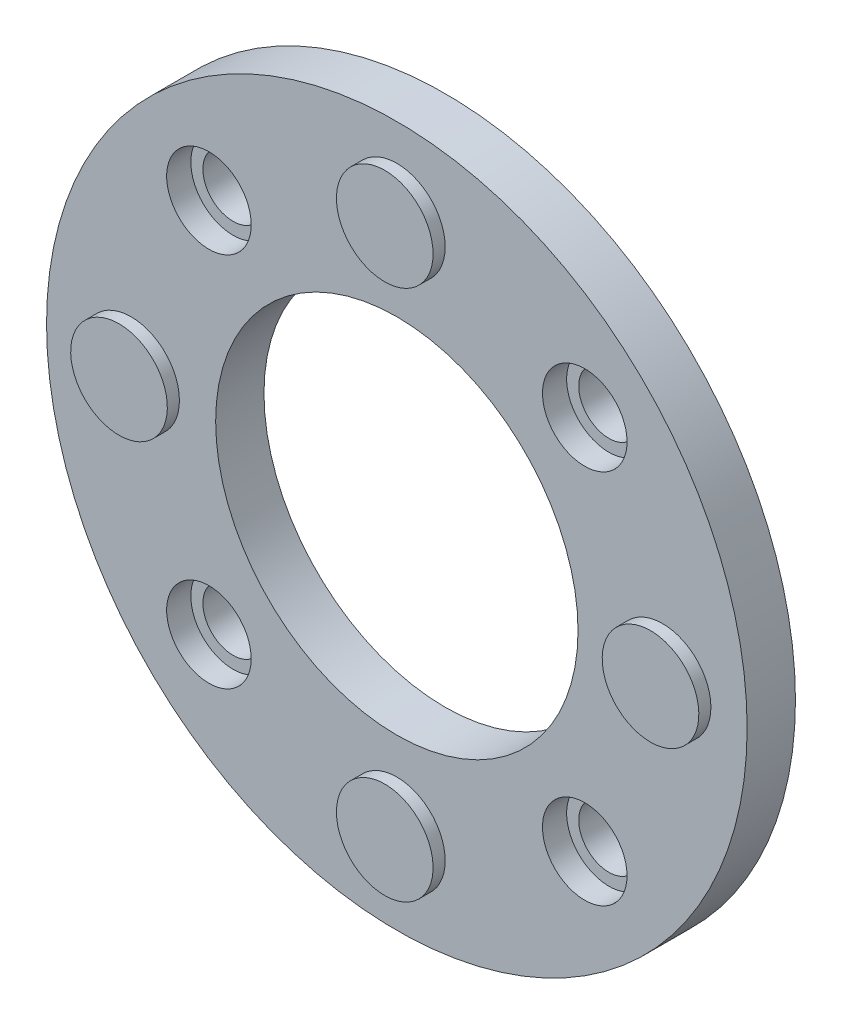
SolidWorks part; units mm, degrees
ref_plane "前视基准面" through (0, 0, 0) normal (0, 0, 1) x (1, 0, 0)
ref_plane "上视基准面" through (0, 0, 0) normal (0, 1, 0) x (1, 0, 0)
ref_plane "右视基准面" through (0, 0, 0) normal (1, 0, 0) x (0, 0, -1)
sketch "草图1" plane through (0, 0, 0) normal (0, 0, 1) x (1, 0, 0)
  circle A0 centre (0, 0) radius 15
  circle A1 centre (0, 0) radius 29
  dimension "D1" = 30
  dimension "D2" = 58
extrude "凸台-拉伸1" add sketch "草图1" along normal mid plane 4
sketch "草图2" plane through (0, 0, 0) normal (0, 0, 1) x (1, 0, 0)
  line L0 (0, -2.2) -> (0, 2.2) construction
  line L1 (2.2, 0) -> (-2.2, 0) construction
  circle A0 centre (0, 22) radius 4
  dimension "D1" = 8
  dimension "D2" = 22
extrude "凸台-拉伸2" add sketch "草图2" along normal mid plane 6
sketch "草图3" plane through (0, 0, -3) normal (0, 0, -1) x (-1, 0, 0)
  circle A0 centre (0, 22) radius 2.5
  dimension "D1" = 5
extrude "切除-拉伸1" cut sketch "草图3" against normal blind 4.5
pattern_circular "阵列(圆周)1" count 4 over 360 about axis through (0, 0, 0) along (0, 0, 1) of "凸台-拉伸2", "切除-拉伸1"
sketch "草图4" plane through (0, 0, 2) normal (0, 0, 1) x (1, 0, 0)
  line L0 (0, 0) -> (-15.5563, 15.5563) construction
  line L1 (0, -3.3) -> (0, 3.3) construction
  point P6 (-15.5563, 15.5563)
  dimension "D1" = 45
  dimension "D2" = 22
hole_wizard "孔1" positions "草图4" profile "草图5" legacy end condition through all
sketch "草图5" plane through (-15.5563, 15.5563, 2) normal (1, 0, 0) x (0, -1, 0)
  line L0 (0, 0) -> (0, 5)
  line L1 (0, 5) -> (2.5, 5)
  line L2 (2.5, 5) -> (2.5, 2)
  line L3 (2.5, 2) -> (3.5, 2)
  line L4 (3.5, 2) -> (3.5, 0)
  line L5 (3.5, 0) -> (0, 0)
  line L6 (0, 110) -> (0, -10) construction
  dimension "直径" = 5
  dimension "深度" = 5
  dimension "柱坑直径" = 7
  dimension "柱坑深度" = 2
sketch "草图6" plane through (0, 0, -2) normal (0, 0, -1) x (-1, 0, 0)
  circle A0 centre (15.5563, 15.5563) radius 3.5
  circle A1 centre (15.5563, 15.5563) radius 2.5 construction
  circle A2 centre (15.5563, 15.5563) radius 2.5
  dimension "D1" = 7
extrude "凸台-拉伸3" add sketch "草图6" along normal up to surface (1 mm away) up to face at (-2.5, 22, -3)
pattern_circular "阵列(圆周)2" count 4 over 360 about axis through (0, 0, 0) along (0, 0, 1) of "凸台-拉伸3", "孔1"
